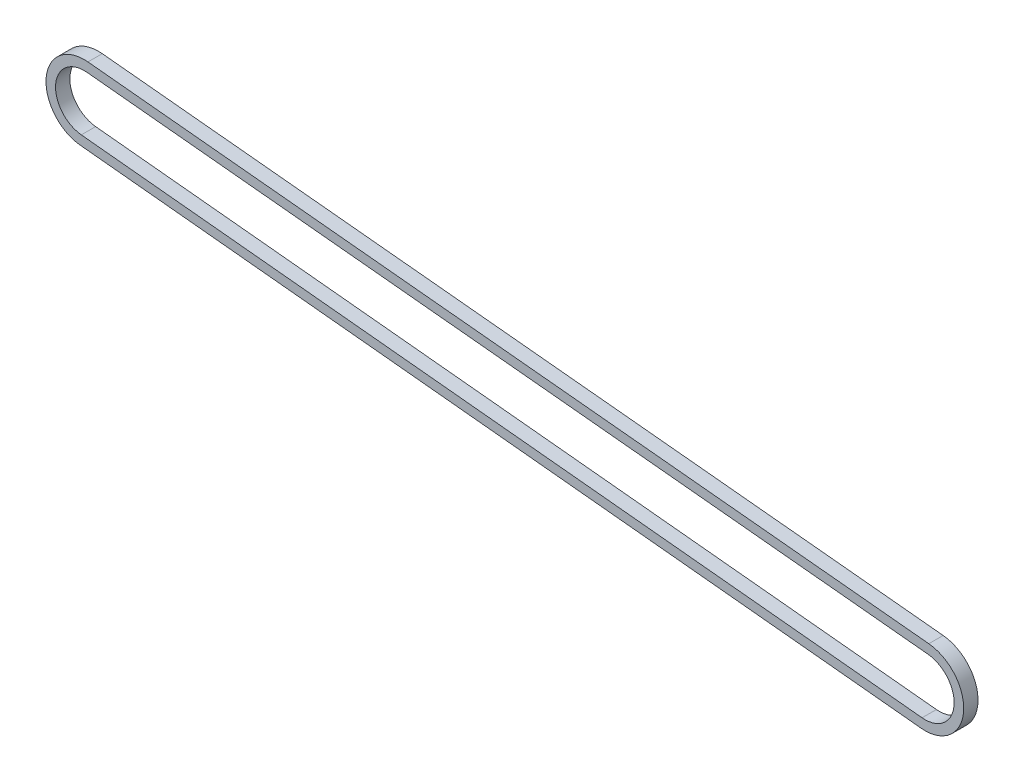
SolidWorks part; units mm, degrees
ref_plane "Front Plane" through (0, 0, 0) normal (0, 0, 1) x (1, 0, 0)
ref_plane "Top Plane" through (0, 0, 0) normal (0, 1, 0) x (1, 0, 0)
ref_plane "Right Plane" through (0, 0, 0) normal (1, 0, 0) x (0, 0, -1)
sketch "Sketch2" plane through (-30.527, 76.3304, 0) normal (0, 0, 1) x (1, 0, 0)
  line L0 (0, 0) -> (1, 0) construction
  line L1 (0, 0) -> (0, 1) construction
  line L2 (-0.6107, -6.0794) -> (-176.7825, 11.6175)
  line L3 (-175.5905, 23.5582) -> (0.6031, 6.0802)
  arc A0 (0.6031, 6.0802) -> (-0.6107, -6.0794) centre (0, 0) cw
  arc A1 (-176.7825, 11.6175) -> (-175.5905, 23.5582) centre (-176.1828, 17.5875) cw
extrude "Extrude-Thin1" add sketch "Sketch2" along normal blind 3 thin thin type one direction wall 2
